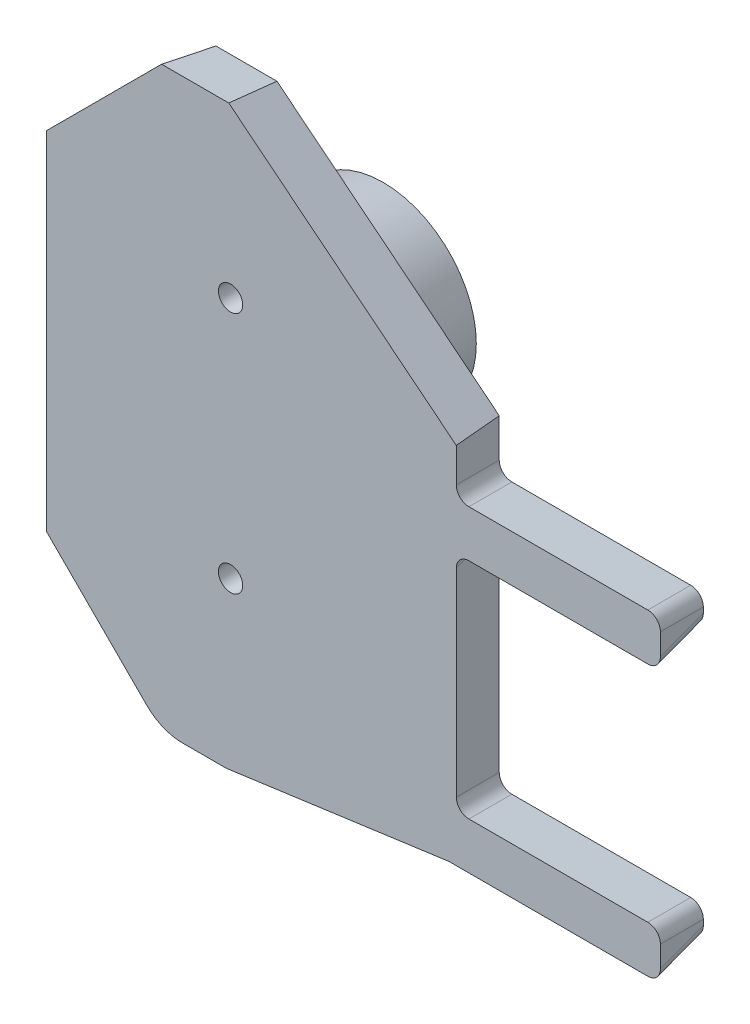
SolidWorks part; units mm, degrees
material "5052-H36"
ref_plane "Plano frontal" through (0, 0, 0) normal (0, 0, 1) x (1, 0, 0)
ref_plane "Plano superior" through (0, 0, 0) normal (0, 1, 0) x (1, 0, 0)
ref_plane "Plano direito" through (0, 0, 0) normal (1, 0, 0) x (0, 0, -1)
sketch "Esboço1" plane through (0, 0, 0) normal (0, 0, 1) x (1, 0, 0)
  line L0 (79.1281, 0) -> (0, 0) construction
  line L3 (4.9801, 55) -> (32.742, 55) construction
  line L6 (32.742, 55) -> (-22.7817, 55) construction
  line L12 (-22.7817, 55) -> (-44.3754, 33.4063)
  line L14 (-44.3754, -33.4063) -> (-22.7817, -55)
  line L15 (-22.7817, -55) -> (32.742, -55) construction
  line L18 (393.8557, 316.0739) -> (396.402, 318.6203) [skipped]
  line L19 (55, 501.996) -> (55, 520.8093) [skipped]
  line L20 (-316.0739, 393.8557) -> (-318.6203, 396.402) [skipped]
  line L21 (32.742, 55) -> (32.742, 20) construction
  line L22 (32.742, -49) -> (32.742, -55) construction
  line L23 (32.742, -49) -> (72.742, -49)
  line L25 (32.742, -43) -> (72.742, -43)
  line L26 (72.742, -49) -> (72.742, -43)
  line L27 (32.742, 4) -> (32.742, -43)
  line L28 (32.742, 4) -> (72.742, 4)
  line L30 (32.742, 10) -> (72.742, 10)
  line L31 (72.742, 4) -> (72.742, 10)
  line L32 (-44.3754, 33.4063) -> (-44.3754, -33.4063)
  line L33 (32.742, 55) -> (-10.8258, 55) construction
  line L34 (-55, 7.7563) -> (-55, -6.3461) [skipped]
  line L35 (-10.8258, 55) -> (32.742, 20)
  line L36 (32.742, 20) -> (32.742, 55) construction
  line L37 (32.742, 20) -> (32.742, 10)
  line L38 (-22.7817, 55) -> (-10.8258, 55)
  line L39 (-10.8258, -55) -> (32.742, -49)
  line L40 (32.742, -49) -> (32.742, -55) construction
  line L41 (32.742, -55) -> (-10.8258, -55) construction
  line L42 (-22.7817, -55) -> (-10.8258, -55)
  circle A0 centre (0, 0) radius 15 construction
  arc A3 (4.9801, 55) -> (0, -55.225) centre (0, 0) ccw construction
  point P14 (4.9801, 55)
  dimension "D1" = 30
  dimension "D2" = 35
  dimension "D5" = 110
  dimension "D3" = 43.5679
  dimension "D4" = 10
  dimension "D6" = 40
  dimension "D7" = 6
  dimension "D8" = 6
  dimension "D9" = 45
  dimension "D10" = 43.5679
  dimension "D11" = 6
extrude "Ressalto-extrusão1" add sketch "Esboço1" along normal blind 10 draft 9 draft outward yes
sketch "Esboço2" plane through (0, 0, 0) normal (0, 0, 1) x (1, 0, 0)
  circle A1 centre (-20, 0) radius 23
  dimension "D1" = 46
  dimension "D2" = 20
extrude "Ressalto-extrusão2" add sketch "Esboço2" against normal blind 30 draft 9
fillet "Filete1" radius 10 1 edges at (-23.1098, -55.7919, 5)
fillet "Filete2" radius 2.5 7 edges at (33.534, -42.2081, 5) (33.534, 10.7919, 5) (33.534, 3.2081, 5) (73.534, 3.2081, 5) (73.534, 10.7919, 5) (73.534, -49.7919, 5) (73.534, -42.2081, 5)
scale "Escala1" bodies to scale 108 scale about centroid uniform scaling yes scale factor 1.05
sketch "Esboço3" plane through (0, 0, 10.5634) normal (0, 0, 1) x (1, 0, 0)
  line L0 (-10, 25) -> (-10, -25) construction
  circle A0 centre (-10, 25) radius 2.5
  circle A3 centre (-10, -25) radius 2.5
  point P0 (-10, 0)
  dimension "D2" = 5
  dimension "D3" = 50
  dimension "D1" = 10
extrude "Corte-extrusão1" cut sketch "Esboço3" against normal blind 5
move or copy body "Corpo-Converter em corpo de malha1" [suppressed] bodies to move or copy 109 copy no translate (0, 0, 0) parameters "D1"=0, "D2"=0, "D3"=0
